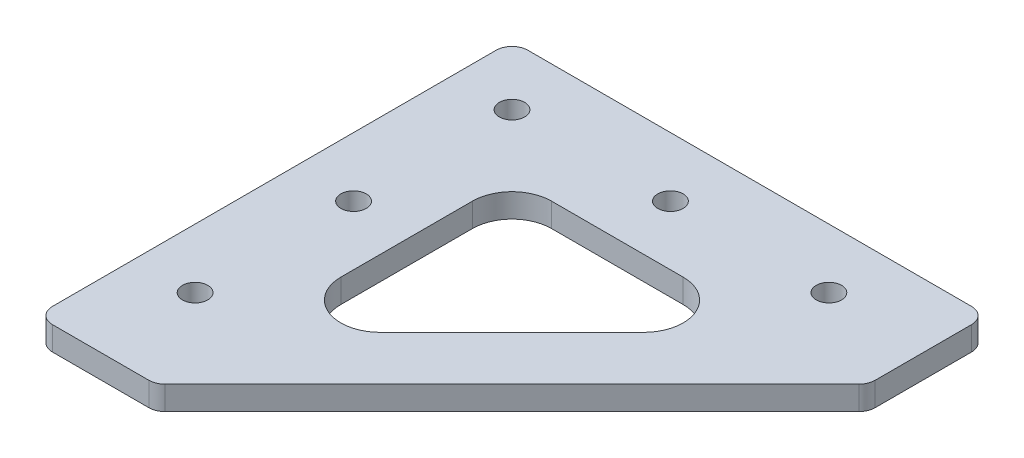
SolidWorks part; units mm, degrees
ref_plane "前视基准面" through (0, 0, 0) normal (0, 0, 1) x (1, 0, 0)
ref_plane "上视基准面" through (0, 0, 0) normal (0, 1, 0) x (1, 0, 0)
ref_plane "右视基准面" through (0, 0, 0) normal (1, 0, 0) x (0, 0, -1)
other "Configuration Table"
sketch "草图1" plane through (0, 0, 0) normal (0, 1, 0) x (1, 0, 0)
  line L0 (0, 0) -> (0, -45) construction
  line L1 (0, -45) -> (-15, -45)
  line L2 (-15, -45) -> (-15, 15)
  line L3 (-15, 15) -> (45, 15)
  line L4 (45, 15) -> (45, 0)
  line L5 (45, 0) -> (0, 0) construction
  line L6 (0, -45) -> (45, 0)
  line L7 (0, -33.6863) -> (0, 0)
  line L8 (0, 0) -> (33.6863, 0)
  line L9 (33.6863, 0) -> (0, -33.6863)
  circle A0 centre (-7.5, -12.5) radius 1.6
  circle A1 centre (-7.5, -32.5) radius 1.6
  circle A4 centre (-7.5, 7.5) radius 1.6
  circle A5 centre (12.5, 7.5) radius 1.6
  circle A7 centre (32.5, 7.5) radius 1.6
  dimension "D8" = 3.2
  dimension "D11" = 3.2
  dimension "D16" = 3.2
  dimension "D1" = 15
  dimension "D2" = 15
  dimension "D3" = 45
  dimension "D4" = 45
  dimension "D5" = 8
  dimension "D6" = 7.5
  dimension "D7" = 20
  dimension "D10" = 20
  dimension "D12" = 7.5
  dimension "D13" = 7.5
  dimension "D15" = 20
  dimension "D9" = 7.5
  dimension "D14" = 3
extrude "凸台-拉伸1" add sketch "草图1" along normal blind 3
fillet "圆角1" radius 2 5 edges at (-15, 1.5, 45) (-15, 1.5, -15) (45, 1.5, -15) (45, 1.5, 0) (0, 1.5, 45)
fillet "圆角2" radius 5 3 edges at (0, 1.5, 0) (0, 1.5, 33.6863) (33.6863, 1.5, 0)
ref_plane "基准面1" through (-20, 0, 0) normal (1, 0, 0) x (0, 0, -1)
